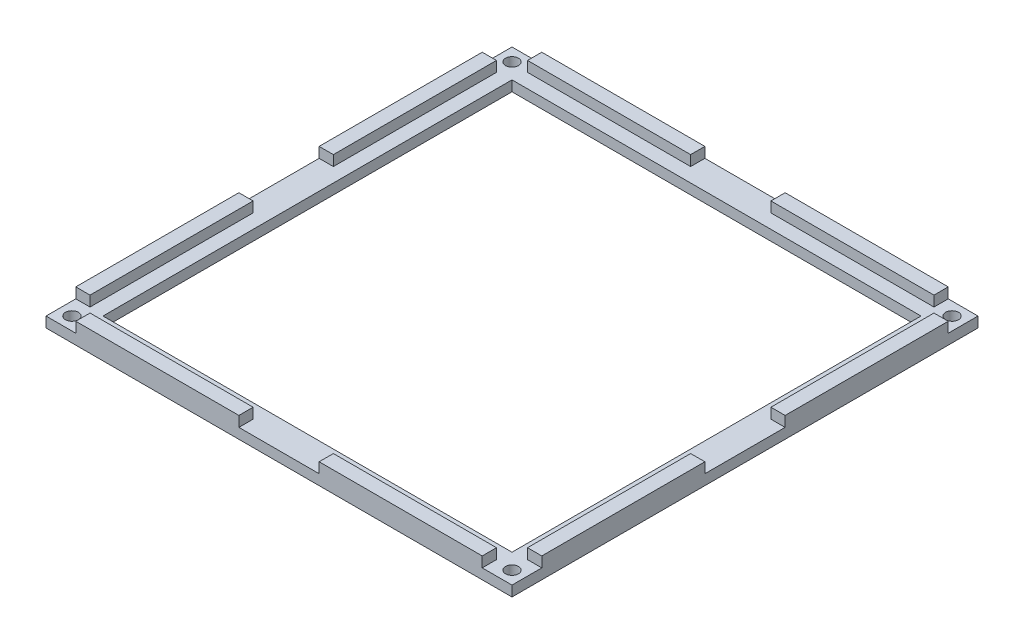
SolidWorks part; units mm, degrees
ref_plane "Alzado" through (0, 0, 0) normal (0, 0, 1) x (1, 0, 0)
ref_plane "Planta" through (0, 0, 0) normal (0, 1, 0) x (1, 0, 0)
ref_plane "Vista lateral" through (0, 0, 0) normal (1, 0, 0) x (0, 0, -1)
sketch "Croquis1" plane through (0, 0, 0) normal (0, 1, 0) x (1, 0, 0)
  line L0 (0, 180) -> (180, 0) construction
  line L1 (0, 0) -> (180, 0)
  line L2 (0, 0) -> (0, 180)
  line L3 (0, 180) -> (180, 180)
  line L4 (180, 0) -> (180, 180)
  line L5 (0, 0) -> (180, 180) construction
  line L6 (5, 90) -> (90, 90) construction
  line L7 (5, 175) -> (175, 175) construction
  line L8 (5, 175) -> (5, 5) construction
  line L9 (5, 5) -> (175, 5) construction
  line L10 (175, 175) -> (175, 5) construction
  line L12 (169, 11) -> (11, 11)
  line L13 (169, 11) -> (169, 169)
  line L14 (169, 169) -> (11, 169)
  line L15 (11, 11) -> (11, 169)
  line L16 (169, 11) -> (11, 169) construction
  line L17 (169, 169) -> (11, 11) construction
  circle A0 centre (5, 175) radius 2.5
  circle A1 centre (175, 175) radius 2.5
  circle A2 centre (175, 5) radius 2.5
  circle A3 centre (5, 5) radius 2.5
  dimension "D2" = 5
  dimension "D1" = 180
  dimension "D3" = 170
  dimension "D4" = 4
  dimension "D5" = 158
extrude "Saliente-Extruir1" add sketch "Croquis1" along normal blind 4
sketch "Croquis2" plane through (0, 4, 0) normal (0, 1, 0) x (1, 0, 0)
  line L0 (0, 180) -> (0, 0) construction
  line L1 (0, 105.5) -> (5.5, 105.5)
  line L2 (0, 105.5) -> (0, 168.5)
  line L3 (0, 168.5) -> (5.5, 168.5)
  line L4 (5.5, 105.5) -> (5.5, 168.5)
  line L5 (180, 180) -> (0, 180) construction
  line L6 (11.5, 180) -> (74.5, 180)
  line L7 (11.5, 180) -> (11.5, 174.5)
  line L8 (11.5, 174.5) -> (74.5, 174.5)
  line L9 (74.5, 180) -> (74.5, 174.5)
  line L10 (0, 137) -> (5.5, 137) construction
  line L11 (5.5, 137) -> (11, 137) construction
  line L12 (11, 169) -> (11, 11) construction
  line L13 (43, 180) -> (43, 174.5) construction
  line L14 (43, 174.5) -> (43, 169) construction
  line L15 (169, 169) -> (11, 169) construction
  line L16 (11, 90) -> (0, 90) construction
  line L17 (5.5, 90) -> (5.5, 105.5) construction
  line L18 (90, 169) -> (90, 180) construction
  line L19 (90, 174.5) -> (74.5, 174.5) construction
  line L20 (11, 169) -> (169, 11) construction
  line L21 (11, 11) -> (169, 169) construction
  line L22 (105.5, 180) -> (168.5, 180)
  line L23 (105.5, 180) -> (105.5, 174.5)
  line L24 (105.5, 174.5) -> (168.5, 174.5)
  line L25 (168.5, 180) -> (168.5, 174.5)
  line L26 (180, 168.5) -> (174.5, 168.5)
  line L27 (180, 168.5) -> (180, 105.5)
  line L28 (180, 105.5) -> (174.5, 105.5)
  line L29 (174.5, 168.5) -> (174.5, 105.5)
  line L30 (180, 74.5) -> (180, 11.5)
  line L31 (180, 74.5) -> (174.5, 74.5)
  line L32 (174.5, 74.5) -> (174.5, 11.5)
  line L33 (180, 11.5) -> (174.5, 11.5)
  line L34 (168.5, 0) -> (168.5, 5.5)
  line L35 (168.5, 0) -> (105.5, 0)
  line L36 (105.5, 0) -> (105.5, 5.5)
  line L37 (168.5, 5.5) -> (105.5, 5.5)
  line L38 (74.5, 0) -> (11.5, 0)
  line L39 (74.5, 0) -> (74.5, 5.5)
  line L40 (74.5, 5.5) -> (11.5, 5.5)
  line L41 (11.5, 0) -> (11.5, 5.5)
  line L42 (0, 11.5) -> (5.5, 11.5)
  line L43 (0, 11.5) -> (0, 74.5)
  line L44 (0, 74.5) -> (5.5, 74.5)
  line L45 (5.5, 11.5) -> (5.5, 74.5)
  dimension "D1" = 63
  dimension "D2" = 15.5
  dimension "D3" = 4
extrude "Saliente-Extruir2" add sketch "Croquis2" along normal blind 4 contours L2 L1 L4 L3 | L42 L45 L44 L43 | L38 L41 L40 L39 | L34 L37 L36 L35 | L30 L33 L32 L31 | L26 L29 L28 L27 | L22 L25 L24 L23 | L7 L6 L9 L8
